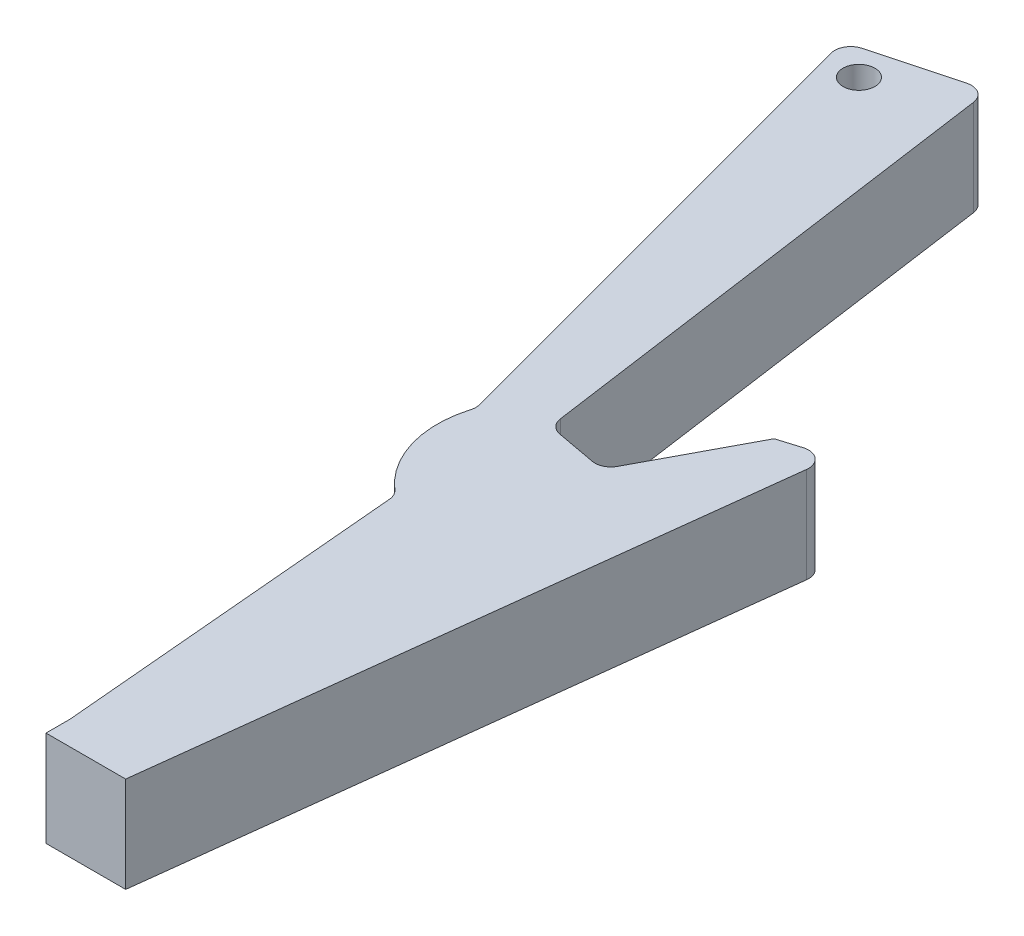
SolidWorks part; units mm, degrees
ref_plane "Front Plane" through (0, 0, 0) normal (0, 0, 1) x (1, 0, 0)
ref_plane "Top Plane" through (0, 0, 0) normal (0, 1, 0) x (1, 0, 0)
ref_plane "Right Plane" through (0, 0, 0) normal (1, 0, 0) x (0, 0, -1)
sketch "Sketch1" plane through (0, 0, 0) normal (0, 1, 0) x (1, 0, 0)
  line L0 (9.324, 44.5766) -> (-47.642, 44.5766) construction
  line L1 (-2.6535, 44.5766) -> (-17.1424, 40.6943)
  line L2 (-17.1424, 40.6943) -> (-0.3191, -22.0909)
  line L3 (-2.6535, 44.5766) -> (6.3411, -19.4234)
  line L4 (6.3411, -19.4234) -> (14.2085, -20.8739)
  line L5 (14.2085, -20.8739) -> (21.7146, -6.7438)
  line L6 (21.7146, -6.7438) -> (27.4517, -4.9874)
  line L7 (27.4517, -4.9874) -> (18.0138, -84.4287)
  line L8 (18.0138, -84.4287) -> (8.0138, -84.4287)
  line L9 (8.0138, -84.4287) -> (8.0138, -81.4287)
  line L10 (8.0138, -81.4287) -> (4.0788, -36.6011)
  arc A0 (-0.3191, -22.0909) -> (4.0788, -36.6011) centre (11.9865, -26.2827) ccw
  dimension "D11" = 13
  dimension "D1" = 15
  dimension "D2" = 15
  dimension "D3" = 90
  dimension "D4" = 65
  dimension "D5" = 83
  dimension "D6" = 64
  dimension "D7" = 8
  dimension "D8" = 16
  dimension "D9" = 6
  dimension "D10" = 80
  dimension "D12" = 45
  dimension "D13" = 3
  dimension "D14" = 10
extrude "Boss-Extrude1" add sketch "Sketch1" along normal blind 12
sketch "Sketch2" plane through (0, 12, 0) normal (0, 1, 0) x (1, 0, 0)
  line L0 (-2.6535, 44.5766) -> (-17.1424, 40.6943) construction
  line L1 (-17.1424, 40.6943) -> (-0.3191, -22.0909) construction
  circle A0 centre (-12.2434, 37.8659) radius 2
  point P2 (0, 0)
  point P3 (-12.9039, 37.6692)
  dimension "D1" = 4
  dimension "D2" = 4
  dimension "D3" = 4
extrude "Cut-Extrude1" cut sketch "Sketch2" against normal through all
fillet "Fillet1" radius 2 7 edges at (4.0788, 6, 36.6011) (-0.3191, 6, 22.0909) (6.3411, 6, 19.4234) (14.2085, 6, 20.8739) (27.4517, 6, 4.9874) (-2.6535, 6, -44.5766) (-17.1424, 6, -40.6943)
